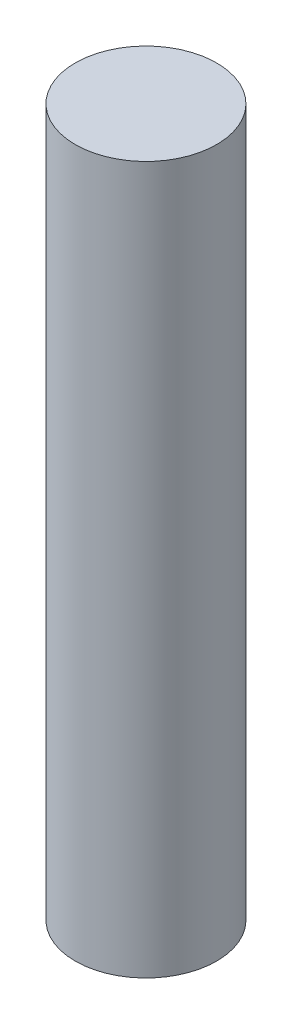
SolidWorks part; units mm, degrees
ref_plane "Front Plane" through (0, 0, 0) normal (0, 0, 1) x (1, 0, 0)
ref_plane "Top Plane" through (0, 0, 0) normal (0, 1, 0) x (1, 0, 0)
ref_plane "Right Plane" through (0, 0, 0) normal (1, 0, 0) x (0, 0, -1)
sketch "Sketch1" plane through (0, 0, 0) normal (0, 1, 0) x (1, 0, 0)
  circle A0 centre (0, 0) radius 5
extrude "Boss-Extrude1" add sketch "Sketch1" along normal blind 50
